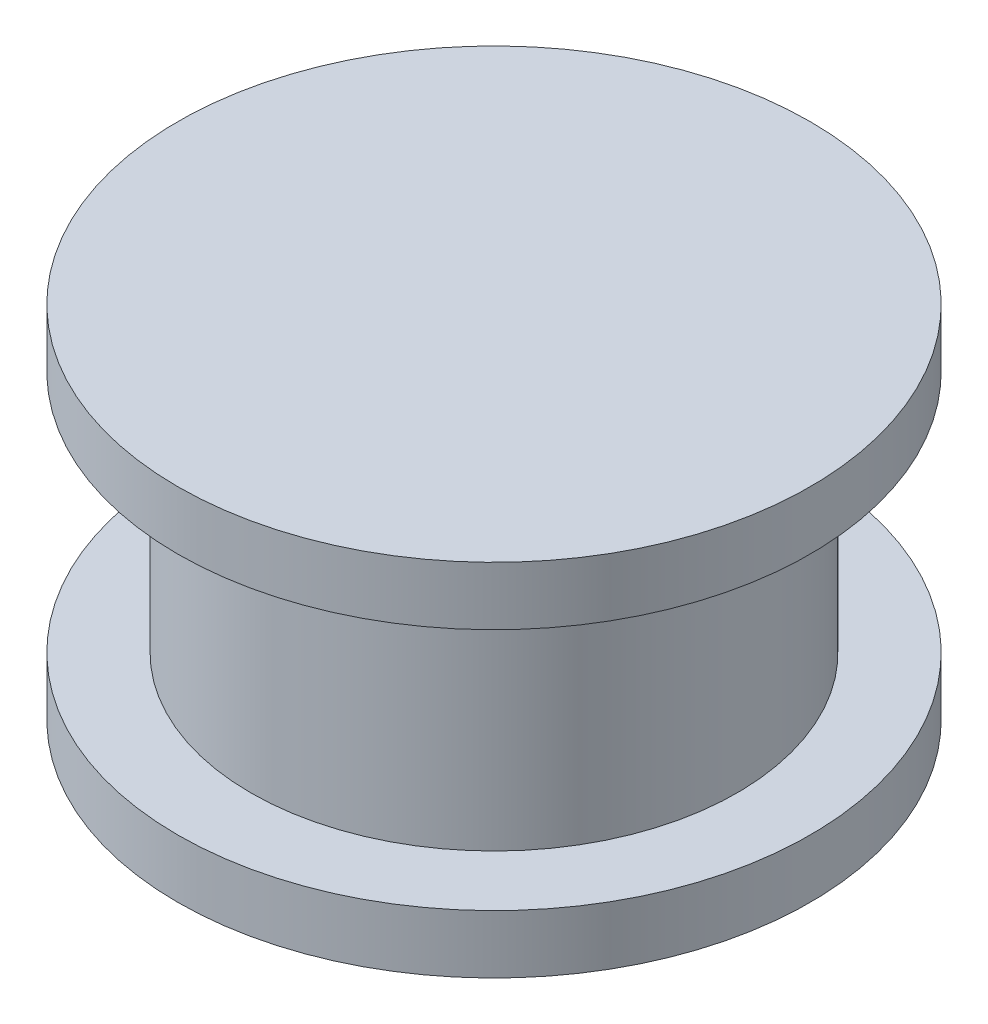
SolidWorks part; units mm, degrees
ref_plane "Front Plane" through (0, 0, 0) normal (0, 0, 1) x (1, 0, 0)
ref_plane "Top Plane" through (0, 0, 0) normal (0, 1, 0) x (1, 0, 0)
ref_plane "Right Plane" through (0, 0, 0) normal (1, 0, 0) x (0, 0, -1)
sketch "Sketch1" plane through (0, 0, 0) normal (0, 1, 0) x (1, 0, 0)
  circle A0 centre (0, 0) radius 5
extrude "Boss-Extrude1" add sketch "Sketch1" along normal blind 5
sketch "Sketch2" plane through (0, 5, 0) normal (0, 1, 0) x (1, 0, 0)
  circle A0 centre (0, 0) radius 6.5
extrude "Boss-Extrude2" add sketch "Sketch2" along normal blind 1.2
sketch "Sketch3" plane through (0, 0, 0) normal (0, -1, 0) x (1, 0, 0)
  circle A1 centre (0, 0) radius 6.5
  circle A2 centre (0, 0) radius 6.5
  dimension "D1" = 0
extrude "Boss-Extrude3" add sketch "Sketch3" along normal blind 1.2
